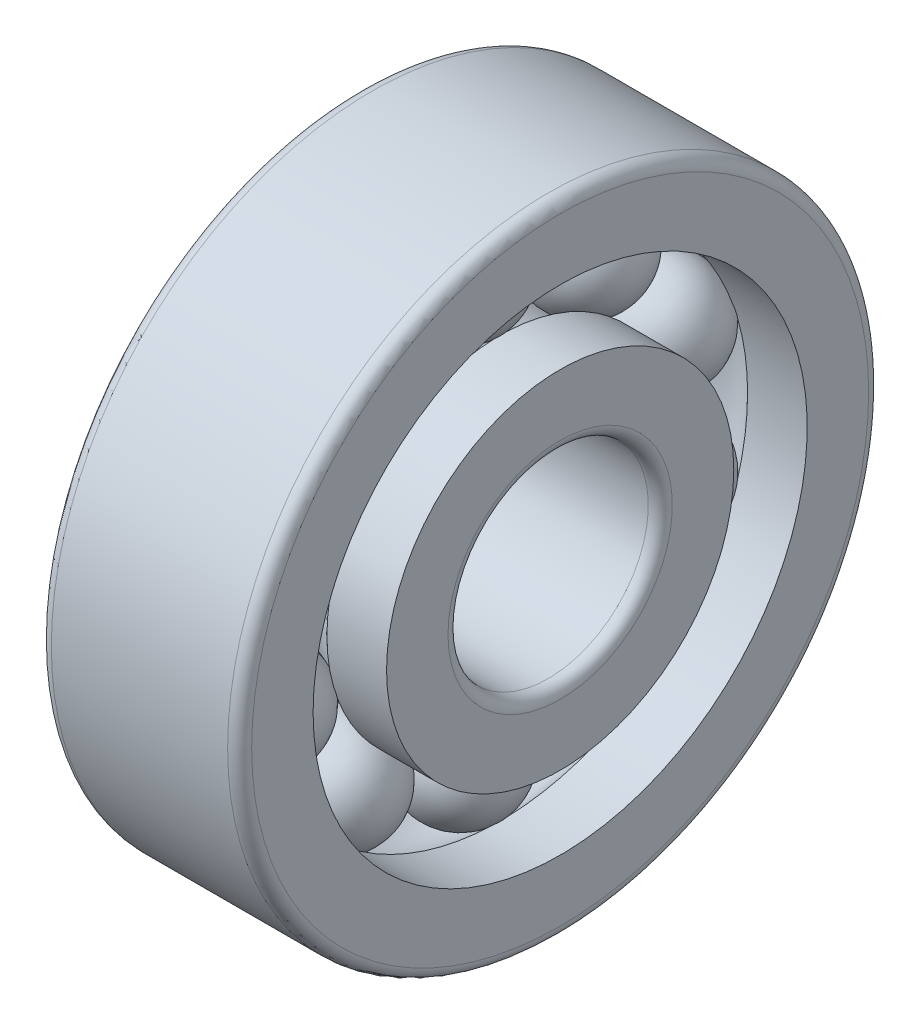
SolidWorks part; units mm, degrees
ref_plane "Front" through (0, 0, 0) normal (0, 0, 1) x (1, 0, 0)
ref_plane "Top" through (0, 0, 0) normal (0, 1, 0) x (1, 0, 0)
ref_plane "Right" through (0, 0, 0) normal (1, 0, 0) x (0, 0, -1)
sketch "Sketch1" plane through (0, 0, 0) normal (0, 0, 1) x (1, 0, 0)
  line L0 (-9.6833, 0) -> (9.8371, 0) construction
  line L1 (-1.375, 5.25) -> (1.375, 5.25)
  line L2 (-4.5966, 5.25) -> (4.6657, 5.25) construction
  arc A0 (1.375, 5.25) -> (-1.375, 5.25) centre (0, 5.25) ccw
  dimension "dia" = 2.75
  dimension "d0" = 10.5
revolve "Revolve1" add sketch "Sketch1" angle 360 about L2
sketch "Sketch2" plane through (0, 0, 0) normal (0, 0, 1) x (1, 0, 0)
  line L0 (-2.5, 4.3333) -> (-2.5, 2.5)
  line L1 (-2.5, 2.5) -> (2.5, 2.5)
  line L2 (2.5, 2.5) -> (2.5, 4.3333)
  line L3 (2.5, 4.3333) -> (1.0114, 4.3333)
  line L4 (-6.9714, 0) -> (8.1665, 0) construction
  line L5 (-6.7058, 5.25) -> (6.7058, 5.25) construction
  line L6 (-1.0114, 4.3333) -> (-2.5, 4.3333)
  arc A0 (-1.0114, 4.3333) -> (1.0114, 4.3333) centre (0, 5.25) ccw
  dimension "B" = 5
  dimension "B/2" = 2.5
  dimension "D5" = 2.73
  dimension "d" = 5
  dimension "D3" = 5.25
  dimension "D4" = 1.8333
revolve "Revolve2" add sketch "Sketch2" angle 360 about L4
sketch "Sketch3" plane through (0, 0, 0) normal (0, 0, 1) x (1, 0, 0)
  line L0 (-8.7107, 0) -> (9.1288, 0) construction
  line L1 (-2.5, 8) -> (2.5, 8)
  line L2 (-2.5, 8) -> (-2.5, 6.1667)
  line L3 (-2.5, 6.1667) -> (-1.0114, 6.1667)
  line L4 (2.5, 8) -> (2.5, 6.1667)
  line L5 (-7.2948, 5.25) -> (7.2948, 5.25) construction
  line L6 (1.0114, 6.1667) -> (2.5, 6.1667)
  arc A0 (1.0114, 6.1667) -> (-1.0114, 6.1667) centre (0, 5.25) ccw
  dimension "D1" = 2.73
  dimension "DD" = 16
  dimension "B" = 5
  dimension "D4" = 5.25
  dimension "D5" = 1.8333
  dimension "B/2" = 2.5
revolve "Revolve3" add sketch "Sketch3" angle 360 about L0
pattern_circular "Circular-Pattern1" count 10 over 360 about axis through (0, 0, 0) along (1, 0, 0) of "Revolve1"
fillet "Fillet1" radius 0.3 4 edges at (-2.5, 0, 2.5) (-2.5, 0, 8) (2.5, 0, 8) (2.5, 0, 2.5)
equation "\"d0@Sketch1\" = ( \"DD@Sketch3\" + \"d@Sketch2\" )  / 2"
equation "\"dia@Sketch1\" =  ( \"DD@Sketch3\" - \"d@Sketch2\" )  / 4"
equation "\"D3@Sketch2\" = ( \"DD@Sketch3\" + \"d@Sketch2\" )  / 2 / 2"
equation "\"D4@Sketch2\" = ( \"DD@Sketch3\" - \"d@Sketch2\" )  / 6"
equation "\"D5@Sketch2\" = \"dia@Sketch1\" - 0.02"
equation "\"B/2@Sketch2\" = \"B@Sketch2\" / 2"
equation "\"D4@Sketch3\" = ( \"DD@Sketch3\" + \"d@Sketch2\" )  / 2 / 2"
equation "\"D5@Sketch3\" = ( \"DD@Sketch3\" - \"d@Sketch2\" )  / 6"
equation "\"B@Sketch3\" = \"B@Sketch2\""
equation "\"B/2@Sketch3\" = \"B@Sketch3\" / 2"
equation "\"D1@Sketch3\" = \"dia@Sketch1\" - 0.02"
equation "\"m@Circular-Pattern1\" = int( 3.14159265 / atn(( \"dia@Sketch1\" / 2) / sqr(( \"DD@Sketch3\" + \"d@Sketch2\" )  / 2 * ( \"DD@Sketch3\" + \"d@Sketch2\" )  / 2/4 - ( \"dia@Sketch1\" / 2) *  ( \"dia@Sketch1\" / 2))))-1"
